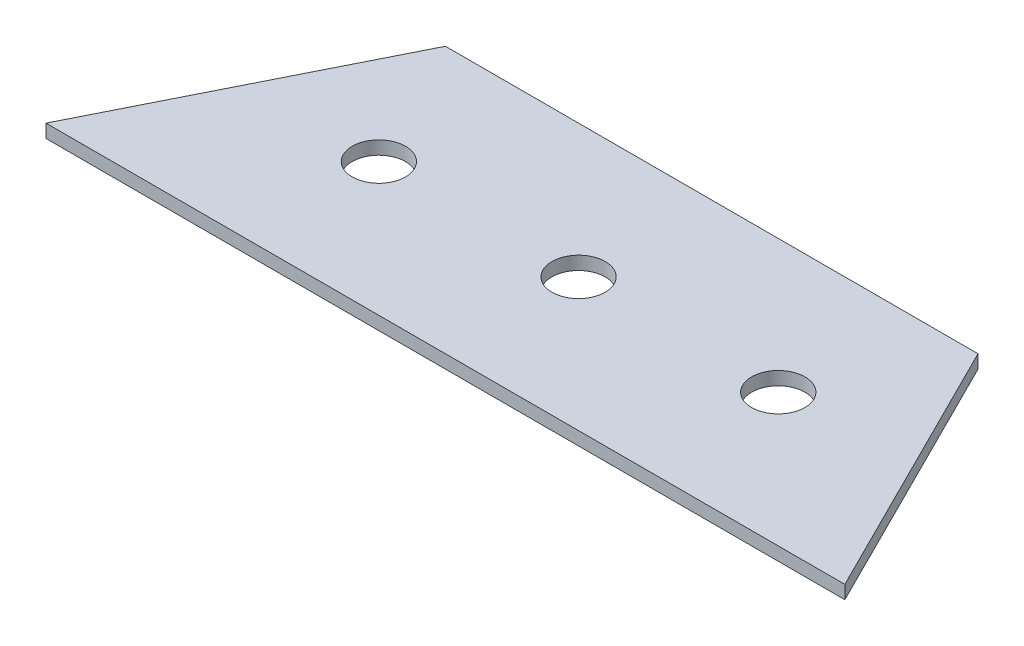
SolidWorks part; units mm, degrees
ref_plane "Front Plane" through (0, 0, 0) normal (0, 0, 1) x (1, 0, 0)
ref_plane "Top Plane" through (0, 0, 0) normal (0, 1, 0) x (1, 0, 0)
ref_plane "Right Plane" through (0, 0, 0) normal (1, 0, 0) x (0, 0, -1)
sketch "Sketch1" plane through (0, 0, 0) normal (0, 1, 0) x (1, 0, 0)
  line L0 (0, 0) -> (-152.4, 0)
  line L1 (-152.4, 0) -> (-127, 50.8)
  line L2 (-127, 50.8) -> (-25.4, 50.8)
  line L3 (-25.4, 50.8) -> (0, 0)
  dimension "D1" = 101.6
  dimension "D2" = 50.8
  dimension "D3" = 152.4
  dimension "D4" = 56.7961
extrude "Boss-Extrude1" add sketch "Sketch1" along normal blind 2.54
sketch "Sketch2" plane through (0, 2.54, 0) normal (0, 1, 0) x (1, 0, 0)
  line L0 (-76.2, 50.8) -> (-76.2, 0) construction
  line L1 (-25.4, 50.8) -> (-127, 50.8) construction
  line L2 (-152.4, 0) -> (0, 0) construction
  circle A0 centre (-76.2, 25.4) radius 5.08
  circle A1 centre (-114.3, 25.4) radius 5.08
  circle A2 centre (-38.1, 25.4) radius 5.08
  dimension "D1" = 38.1
  dimension "D2" = 38.1
  dimension "D3" = 10.16
  dimension "D4" = 10.16
  dimension "D5" = 10.16
extrude "Cut-Extrude1" cut sketch "Sketch2" against normal through all
